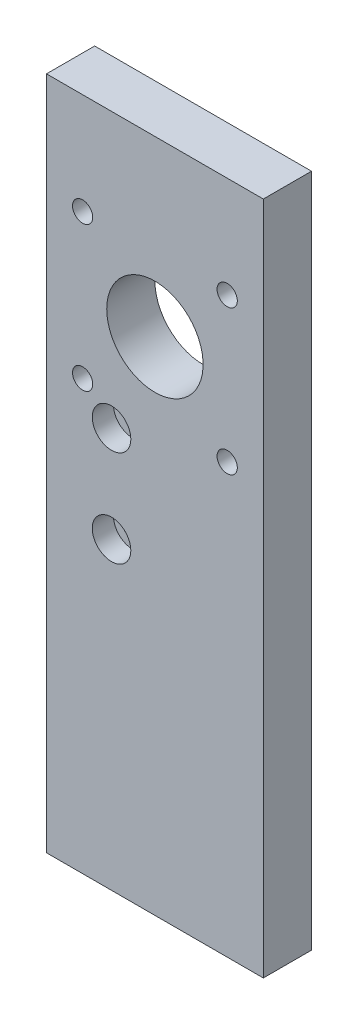
SolidWorks part; units mm, degrees
material "3.3547 (EN-AW 5083)"
ref_plane "Vorne" through (0, 0, 0) normal (0, 0, 1) x (1, 0, 0)
ref_plane "Oben" through (0, 0, 0) normal (0, 1, 0) x (1, 0, 0)
ref_plane "Rechts" through (0, 0, 0) normal (1, 0, 0) x (0, 0, -1)
sketch "Skizze1" plane through (0, 0, 0) normal (0, 0, 1) x (1, 0, 0)
  line L0 (5.5, 0) -> (-5.5, 0) construction
  line L1 (-22.5, 140) -> (22.5, 140)
  line L2 (-22.5, 140) -> (-22.5, 0)
  line L3 (-22.5, 0) -> (22.5, 0)
  line L4 (22.5, 140) -> (22.5, 0)
  line L5 (0, -5.5) -> (0, 5.5) construction
  point P6 (0, 140)
  dimension "D1" = 45
  dimension "D2" = 140
extrude "Aufsatz-Linear austragen1" add sketch "Skizze1" along normal mid plane 10
hole_wizard "Stirnsenkung für M4 Zylinderschraube mit Innensechskant1" positions "Skizze2" profile "Skizze3" counterbore size "M4" standard "DIN" end condition through all
sketch "Skizze2" plane through (0, 0, 5) normal (0, 0, 1) x (1, 0, 0)
  line L0 (5.5, 0) -> (-5.5, 0) construction
  line L1 (0, -5.5) -> (0, 5.5) construction
  point P0 (-9, 83.08)
  dimension "D1" = 83.08
  dimension "D2" = 9
sketch "Skizze3" plane through (-9, 83.08, 5) normal (1, 0, 0) x (0, -1, 0)
  line L0 (0, 0) -> (0, 10)
  line L1 (0, 10) -> (2.25, 10)
  line L3 (2.25, 10) -> (2.25, 4.4)
  line L4 (2.25, 4.4) -> (4, 4.4)
  line L5 (4, 4.4) -> (4, 0)
  line L7 (4, 0) -> (0, 0)
  line L11 (0, -6.35) -> (0, 107.95) construction
  dimension "Bohrerdurchmesser" = 4.5
  dimension "Bohrungstiefe" = 10
  dimension "Senkdurchmesser2" = 8
  dimension "Senktiefe2" = 4.4
hole_wizard "M5 Gewindebohrung1" positions "Skizze4" profile "Skizze5" tap size "M5" standard "DIN" end condition through all
sketch "Skizze4" plane through (0, 0, 5) normal (0, 0, 1) x (1, 0, 0)
  line L1 (-15, 89) -> (15, 89) construction
  line L2 (-15, 89) -> (-15, 119) construction
  line L3 (-15, 119) -> (15, 119) construction
  line L4 (15, 89) -> (15, 119) construction
  line L5 (-15, 89) -> (15, 119) construction
  line L6 (-15, 119) -> (15, 89) construction
  line L8 (0, -5.5) -> (0, 5.5) construction
  line L9 (5.5, 0) -> (-5.5, 0) construction
  point P2 (15, 119)
  point P127 (-15, 89)
  point P128 (-15, 119)
  point P129 (15, 89)
  point P134 (0, 104)
  dimension "D1" = 30
  dimension "D2" = 104
sketch "Skizze5" plane through (15, 119, 5) normal (1, 0, 0) x (0, -1, 0)
  line L0 (0, 0) -> (0, 10)
  line L1 (0, 10) -> (2.1, 10)
  line L2 (2.1, 10) -> (2.1, 0)
  line L5 (2.1, 0) -> (0, 0)
  line L11 (0, -6.35) -> (0, 107.95) construction
  dimension "Bohrerdurchmesser" = 4.2
  dimension "Bohrungstiefe" = 10
cosmetic thread "Bohrungsgewinde1" parameters "D2"=5
cosmetic thread "Bohrungsgewinde2" parameters "D2"=5
cosmetic thread "Bohrungsgewinde3" parameters "D2"=5
cosmetic thread "Bohrungsgewinde4" parameters "D2"=5
pattern_linear "Lineares Muster1" count 2 spacing 20 along (0, -1, 0) of "Stirnsenkung für M4 Zylinderschraube mit Innensechskant1"
hole_wizard "M5 Gewindebohrung2" positions "Skizze6" profile "Skizze7" tap size "M5" standard "DIN"
sketch "Skizze6" plane through (0, 0, 0) normal (0, -1, 0) x (-1, 0, 0)
  point P0 (0, 0)
sketch "Skizze7" plane through (0, 0, 0) normal (1, 0, 0) x (0, 0, -1)
  line L0 (0, 0) -> (0, 15.2618)
  line L1 (0, 15.2618) -> (2.1, 14)
  line L2 (2.1, 14) -> (2.1, 0)
  line L5 (2.1, 0) -> (0, 0)
  line L10 (0, 15.2618) -> (-2.1, 14) construction
  line L11 (0, -6.35) -> (0, 107.95) construction
  dimension "Bohrerdurchmesser" = 4.2
  dimension "Bohrungstiefe" = 14
  dimension "Spitzenwinkel" = 118
cosmetic thread "Bohrungsgewinde5" parameters "D1"=10, "D2"=5
hole_wizard "Ø4.0 (4) Durchmesser Bohrung1" positions "Skizze8" profile "Skizze9" hole size "Ø4.0" standard "DIN"
sketch "Skizze8" plane through (0, 0, 0) normal (0, -1, 0) x (-1, 0, 0)
  line L0 (-24.75, 0) -> (24.75, 0) construction
  line L1 (0, 5.5) -> (0, -5.5) construction
  point P0 (15, 0)
  point P4 (-15, 0)
  dimension "D1" = 15
  dimension "D2" = 15
sketch "Skizze9" plane through (-15, 0, 0) normal (1, 0, 0) x (0, 0, -1)
  line L0 (0, 0) -> (0, 15.2017)
  line L1 (0, 15.2017) -> (2, 14)
  line L2 (2, 14) -> (2, 0)
  line L5 (2, 0) -> (0, 0)
  line L10 (0, 15.2017) -> (-2, 14) construction
  line L11 (0, -6.35) -> (0, 107.95) construction
  dimension "Bohrerdurchmesser" = 4
  dimension "Bohrungstiefe" = 14
  dimension "Spitzenwinkel" = 118
hole_wizard "Ø3.0 (3) Durchmesser Bohrung1" positions "Skizze10" profile "Skizze11" hole size "Ø3.0" standard "DIN"
sketch "Skizze10" plane through (0, 0, -5) normal (0, 0, -1) x (-1, 0, 0)
  line L0 (22.5, 0) -> (-22.5, 0) construction
  line L1 (22.5, 140) -> (22.5, 0) construction
  point P0 (17.5, 76.5)
  point P2 (-2.5, 76.5)
  dimension "D1" = 76.5
  dimension "D2" = 5
  dimension "D3" = 25
sketch "Skizze11" plane through (-17.5, 76.5, -5) normal (1, 0, 0) x (0, 1, 0)
  line L0 (0, 0) -> (0, 8)
  line L1 (0, 8) -> (1.5, 8)
  line L2 (1.5, 8) -> (1.5, 0)
  line L5 (1.5, 0) -> (0, 0)
  line L10 (0, 8) -> (-1.5, 8) construction
  line L11 (0, -6.35) -> (0, 107.95) construction
  dimension "Bohrerdurchmesser" = 3
  dimension "Bohrungstiefe" = 8
  dimension "Spitzenwinkel" = 180
hole_wizard "Ø20.0 (20) Durchmesser Bohrung1" positions "Skizze12" profile "Skizze13" hole size "Ø20.0" standard "DIN" end condition through all
sketch "Skizze12" plane through (0, 0, -5) normal (0, 0, -1) x (-1, 0, 0)
  line L0 (-15, 119) -> (15, 89) construction
  line L2 (15, 119) -> (-15, 89) construction
  point P13 (0, 104)
sketch "Skizze13" plane through (0, 104, -5) normal (1, 0, 0) x (0, 1, 0)
  line L0 (0, 0) -> (0, 10)
  line L1 (0, 10) -> (10, 10)
  line L2 (10, 10) -> (10, 0)
  line L5 (10, 0) -> (0, 0)
  line L11 (0, -6.35) -> (0, 107.95) construction
  dimension "Bohrerdurchmesser" = 20
  dimension "Bohrungstiefe" = 10
